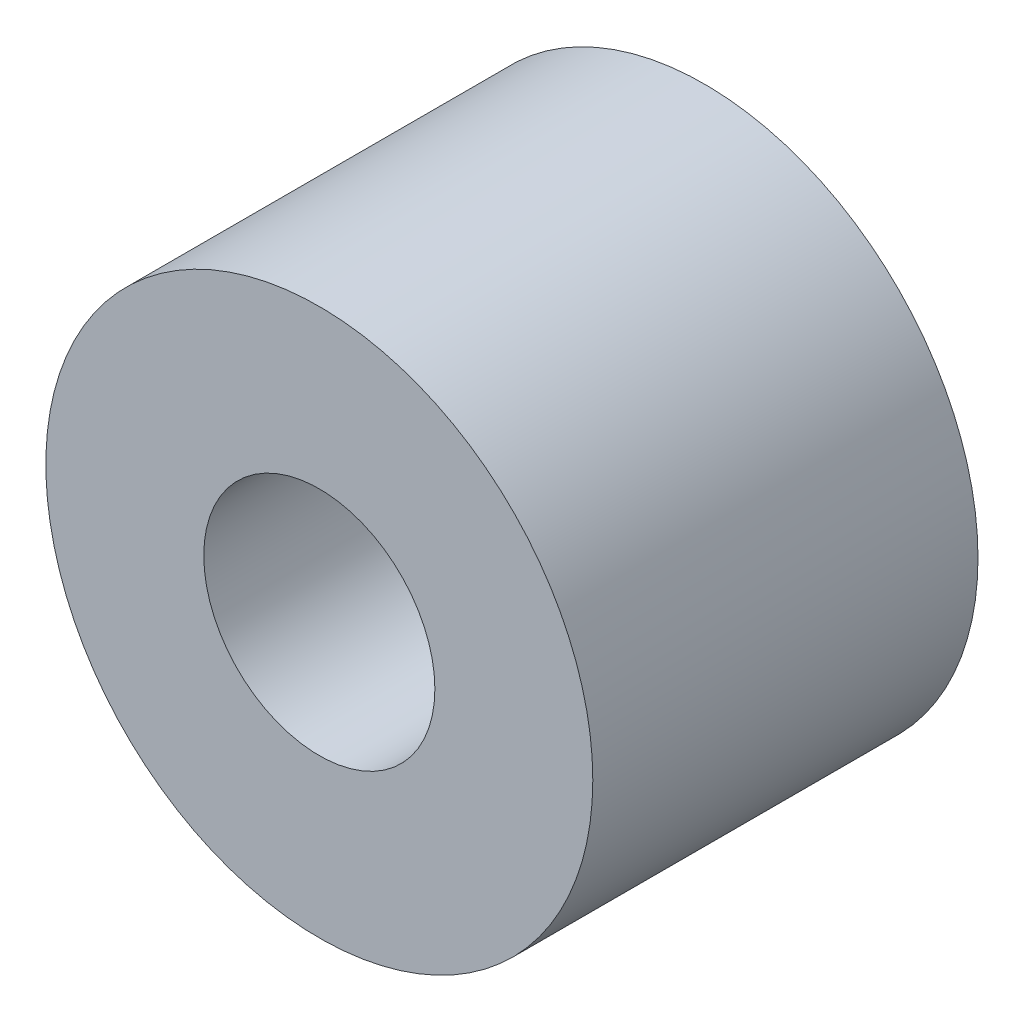
SolidWorks part; units mm, degrees
ref_plane "Front Plane" through (0, 0, 0) normal (0, 0, 1) x (1, 0, 0)
ref_plane "Top Plane" through (0, 0, 0) normal (0, 1, 0) x (1, 0, 0)
ref_plane "Right Plane" through (0, 0, 0) normal (1, 0, 0) x (0, 0, -1)
sketch "Sketch1" plane through (0, 0, 0) normal (0, 0, 1) x (1, 0, 0)
  circle A0 centre (0, 0) radius 14.2
  circle A1 centre (0, 0) radius 6
extrude "Connection_space_only_NO_THREADS_OR_SEALS" add sketch "Sketch1" along normal blind 20
